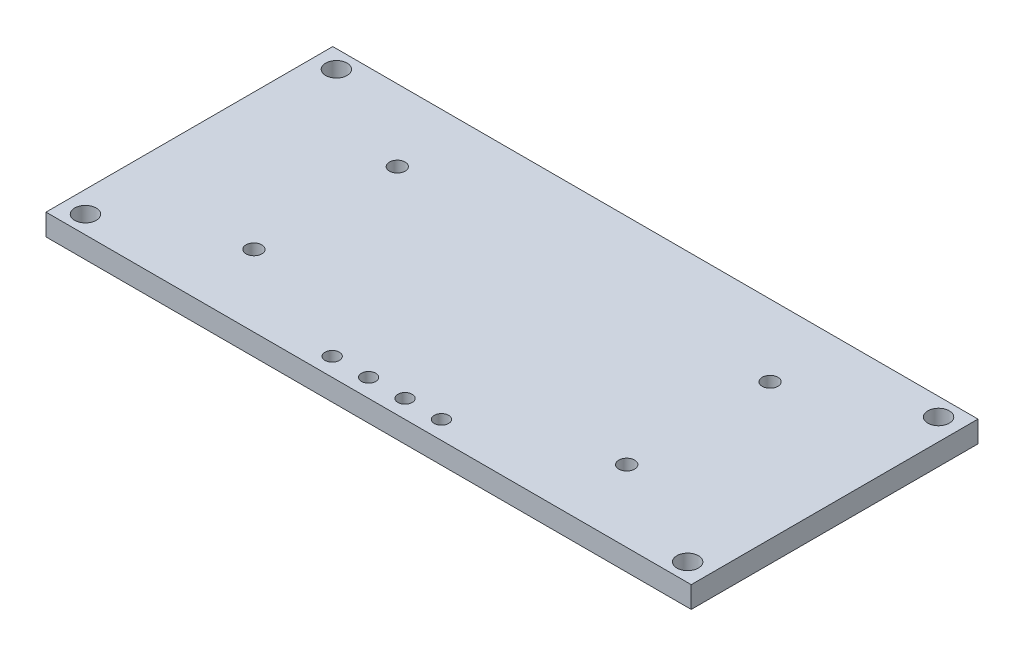
SolidWorks part; units mm, degrees
ref_plane "Front Plane" through (0, 0, 0) normal (0, 0, 1) x (1, 0, 0)
ref_plane "Top Plane" through (0, 0, 0) normal (0, 1, 0) x (1, 0, 0)
ref_plane "Right Plane" through (0, 0, 0) normal (1, 0, 0) x (0, 0, -1)
sketch "Sketch1" plane through (0, 0, 0) normal (0, 1, 0) x (1, 0, 0)
  line L0 (0, 1.9416) -> (0, 0) construction
  line L1 (22.5, -10) -> (-22.5, -10)
  line L2 (22.5, -10) -> (22.5, 10)
  line L3 (22.5, 10) -> (-22.5, 10)
  line L4 (-22.5, -10) -> (-22.5, 10)
  line L5 (22.5, -10) -> (-22.5, 10) construction
  line L6 (22.5, 10) -> (-22.5, -10) construction
  line L7 (0, 0) -> (-1.8577, 0) construction
  circle A0 centre (-21, 8.75) radius 0.75
  circle A1 centre (-21, -8.75) radius 0.75
  circle A2 centre (21, -8.75) radius 0.75
  circle A3 centre (21, 8.75) radius 0.75
  point P0 (0, 0)
  dimension "D3" = 1.5
  dimension "D1" = 45
  dimension "D2" = 20
  dimension "D4" = 17.5
  dimension "D5" = 42
extrude "PCB" add sketch "Sketch1" along normal blind 1.5
sketch "Sketch2" plane through (0, 1.5, 0) normal (0, 1, 0) x (1, 0, 0)
  line L1 (-22.5, -10) -> (22.5, -10) construction
  line L2 (0, 0) -> (0, -2.0527) construction
  line L3 (0, 0) -> (-2.304, 0) construction
  circle A0 centre (-3.81, -8.73) radius 0.5
  circle A1 centre (-1.27, -8.73) radius 0.5
  circle A2 centre (1.27, -8.73) radius 0.5
  circle A3 centre (3.81, -8.73) radius 0.5
  circle A4 centre (13, 5) radius 0.55
  circle A5 centre (13, -5) radius 0.55
  circle A6 centre (-13, -5) radius 0.55
  circle A7 centre (-13, 5) radius 0.55
  dimension "D1" = 1
  dimension "D2" = 1.1
  dimension "D3" = 2.54
  dimension "D4" = 2.54
  dimension "D5" = 2.54
  dimension "D6" = 1.27
  dimension "D7" = 10
  dimension "D8" = 26
extrude "Holes" cut sketch "Sketch2" against normal blind 2
